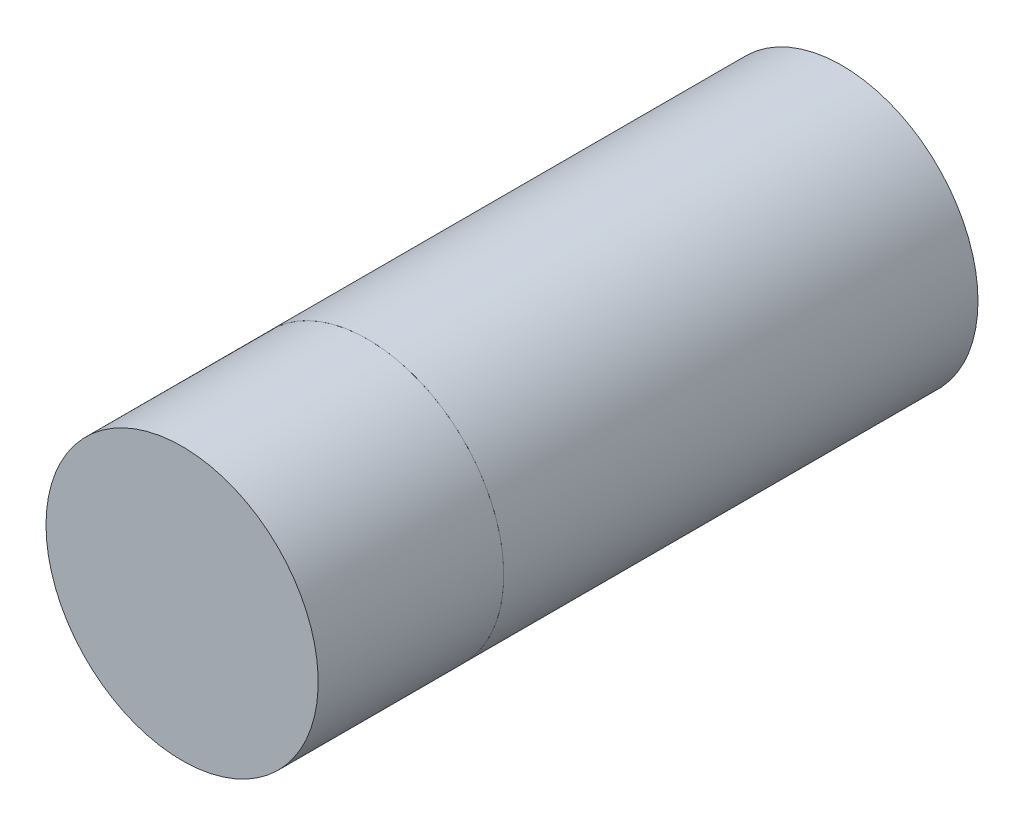
SolidWorks part; units mm, degrees
ref_plane "Front Plane" through (0, 0, 0) normal (0, 0, 1) x (1, 0, 0)
ref_plane "Top Plane" through (0, 0, 0) normal (0, 1, 0) x (1, 0, 0)
ref_plane "Right Plane" through (0, 0, 0) normal (1, 0, 0) x (0, 0, -1)
sketch "Sketch1" plane through (0, 0, 0) normal (0, 0, 1) x (1, 0, 0)
  circle A0 centre (0, 0) radius 33
  dimension "D1" = 66
extrude "Cansat components envelope" add sketch "Sketch1" along normal blind 115
sketch "Sketch2" plane through (0, 0, 115) normal (0, 0, 1) x (1, 0, 0)
  circle A1 centre (0, 0) radius 33
  circle A2 centre (0, 0) radius 33
  dimension "D1" = 0
extrude "Parachute and antennas envelope" add sketch "Sketch2" along normal blind 45 separate body
ref_plane "Plane1" through (0, 0, 80) normal (0, 0, 1) x (1, 0, 0)
